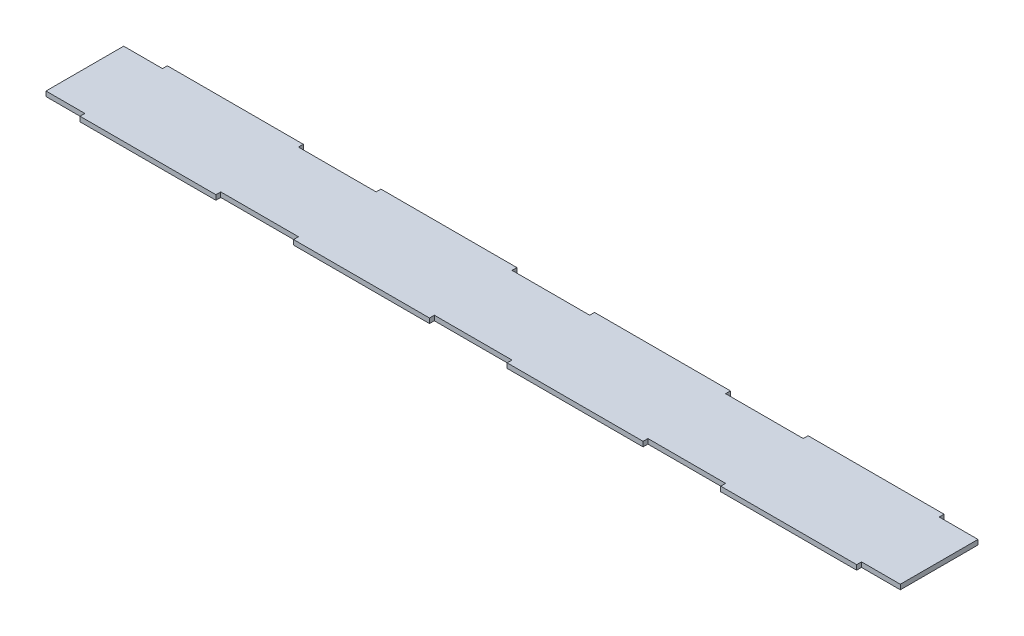
SolidWorks part; units mm, degrees
material "Teak"
ref_plane "Front Plane" through (0, 0, 0) normal (0, 0, 1) x (1, 0, 0)
ref_plane "Top Plane" through (0, 0, 0) normal (0, 1, 0) x (1, 0, 0)
ref_plane "Right Plane" through (0, 0, 0) normal (1, 0, 0) x (0, 0, -1)
sketch "Sketch1" plane through (0, 0, 0) normal (0, 1, 0) x (1, 0, 0)
  line L0 (0, -25.4) -> (0, 25.4)
  line L1 (0, 25.4) -> (25.4, 25.4)
  line L2 (25.4, 25.4) -> (25.4, 28.575)
  line L3 (25.4, 28.575) -> (114.3, 28.575)
  line L4 (114.3, 28.575) -> (114.3, 25.4)
  line L18 (-1000, 0) -> (49000, 0) construction
  line L19 (209.55, -964.44) -> (209.55, 49035.56) construction
  line L36 (114.3, -28.575) -> (114.3, -25.4)
  line L37 (25.4, -28.575) -> (114.3, -28.575)
  line L38 (25.4, -25.4) -> (25.4, -28.575)
  line L39 (0, -25.4) -> (25.4, -25.4)
  line L40 (114.3, 25.4) -> (139.7, 25.4)
  line L41 (114.3, -25.4) -> (139.7, -25.4)
  line L42 (558.8, -25.4) -> (558.8, 25.4)
  line L43 (139.7, 25.4) -> (165.1, 25.4)
  line L44 (165.1, 25.4) -> (165.1, 28.575)
  line L45 (165.1, 28.575) -> (254, 28.575)
  line L46 (254, 28.575) -> (254, 25.4)
  line L47 (254, -28.575) -> (254, -25.4)
  line L48 (165.1, -28.575) -> (254, -28.575)
  line L49 (165.1, -25.4) -> (165.1, -28.575)
  line L50 (139.7, -25.4) -> (165.1, -25.4)
  line L51 (254, 25.4) -> (279.4, 25.4)
  line L52 (254, -25.4) -> (279.4, -25.4)
  line L54 (279.4, 25.4) -> (304.8, 25.4)
  line L55 (304.8, 25.4) -> (304.8, 28.575)
  line L56 (304.8, 28.575) -> (393.7, 28.575)
  line L57 (393.7, 28.575) -> (393.7, 25.4)
  line L58 (393.7, -28.575) -> (393.7, -25.4)
  line L59 (304.8, -28.575) -> (393.7, -28.575)
  line L60 (304.8, -25.4) -> (304.8, -28.575)
  line L61 (279.4, -25.4) -> (304.8, -25.4)
  line L62 (393.7, 25.4) -> (419.1, 25.4)
  line L63 (393.7, -25.4) -> (419.1, -25.4)
  line L65 (419.1, 25.4) -> (444.5, 25.4)
  line L66 (444.5, 25.4) -> (444.5, 28.575)
  line L67 (444.5, 28.575) -> (533.4, 28.575)
  line L68 (533.4, 28.575) -> (533.4, 25.4)
  line L69 (533.4, -28.575) -> (533.4, -25.4)
  line L70 (444.5, -28.575) -> (533.4, -28.575)
  line L71 (444.5, -25.4) -> (444.5, -28.575)
  line L72 (419.1, -25.4) -> (444.5, -25.4)
  line L73 (533.4, 25.4) -> (558.8, 25.4)
  line L74 (533.4, -25.4) -> (558.8, -25.4)
  line L75 (139.7, 0) -> (139.7, 25.4) [skipped]
  line L76 (279.4, -25.4) -> (279.4, 0) [skipped]
  line L77 (419.1, -25.4) -> (419.1, 0) [skipped]
  point P0 (209.55, -28.575)
  point P15 (209.55, 28.575)
  point P23 (419.1, 0)
  point P29 (139.7, 0)
  point P36 (0, 0)
  point P48 (279.4, 0)
  point P61 (419.1, 0)
  dimension "D1" = 25.4
  dimension "D2" = 88.9
  dimension "D3" = 25.4
  dimension "D4" = 44.45
  dimension "D5" = 57.15
  dimension "D6" = 3.175
  dimension "D7" = 4
  dimension "D8" = 95.25
extrude "Boss-Extrude1" add sketch "Sketch1" along normal blind 3.175
